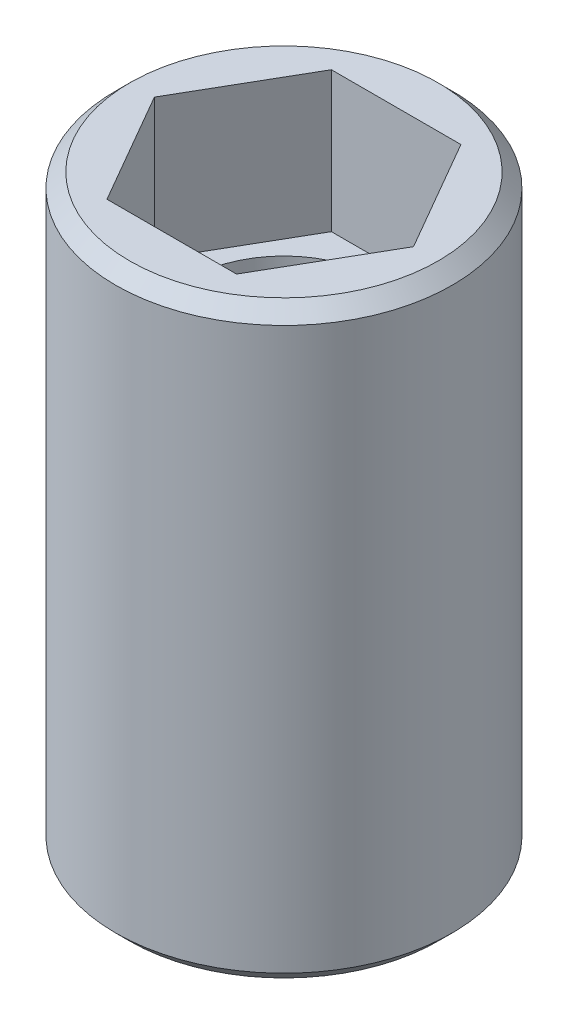
SolidWorks part; units mm, degrees
material "Plain Carbon Steel"
ref_plane "Front Plane" through (0, 0, 0) normal (0, 0, 1) x (1, 0, 0)
ref_plane "Top Plane" through (0, 0, 0) normal (0, 1, 0) x (1, 0, 0)
ref_plane "Right Plane" through (0, 0, 0) normal (1, 0, 0) x (0, 0, -1)
sketch "Sketch1" plane through (0, 0, 0) normal (0, 1, 0) x (1, 0, 0)
  circle A0 centre (0, 0) radius 6
  dimension "D1" = 12
extrude "Boss-Extrude1" add sketch "Sketch1" against normal blind 21
sketch "Sketch2" plane through (0, 0, 0) normal (0, 1, 0) x (1, 0, 0)
  circle A0 centre (0, 0) radius 3.4
  dimension "D1" = 6.8
extrude "Cut-Extrude1" cut sketch "Sketch2" against normal through all
cosmetic thread "Cosmetic Thread1"
sketch "Sketch3" plane through (0, 0, 0) normal (0, 1, 0) x (1, 0, 0)
  line L1 (4.6188, 0) -> (2.3094, 4)
  line L2 (2.3094, 4) -> (-2.3094, 4)
  line L3 (-2.3094, 4) -> (-4.6188, 0)
  line L4 (-4.6188, 0) -> (-2.3094, -4)
  line L5 (-2.3094, -4) -> (2.3094, -4)
  line L6 (2.3094, -4) -> (4.6188, 0)
  circle A0 centre (0, 0) radius 4 construction
  dimension "D1" = 8
extrude "Cut-Extrude2" cut sketch "Sketch3" against normal blind 5
chamfer "Chamfer1" distance 0.5 angle 45 2 edges at (0, 0, 6) (0, -21, 6)
